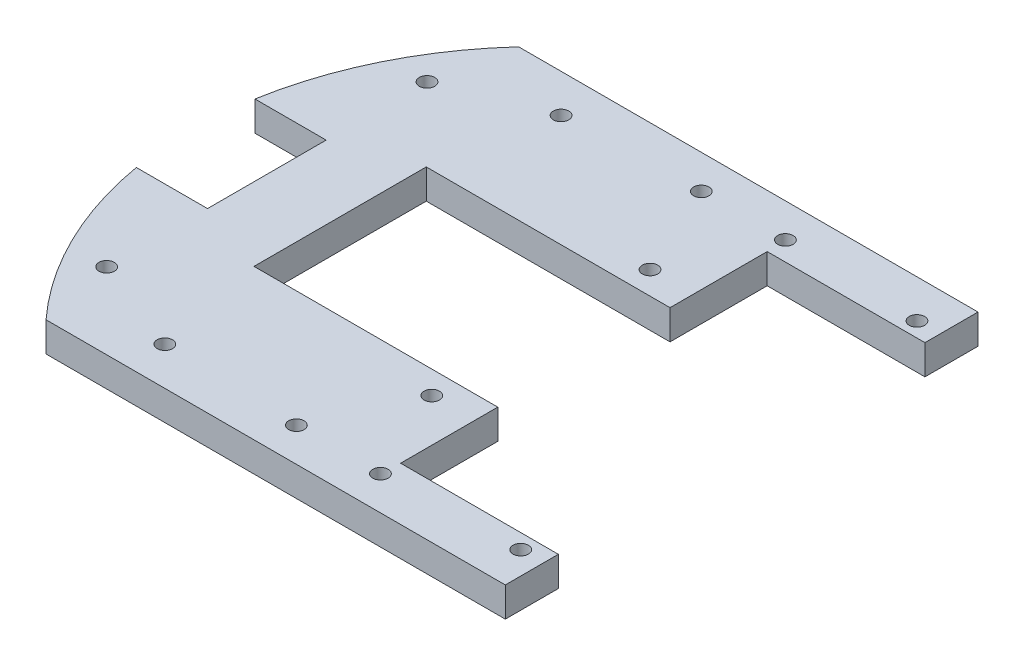
SolidWorks part; units mm, degrees
material "Acrylic (Medium-high impact)"
ref_plane "Front Plane" through (0, 0, 0) normal (0, 0, 1) x (1, 0, 0)
ref_plane "Top Plane" through (0, 0, 0) normal (0, 1, 0) x (1, 0, 0)
ref_plane "Right Plane" through (0, 0, 0) normal (1, 0, 0) x (0, 0, -1)
sketch "Sketch1" plane through (0, 0, 0) normal (0, 1, 0) x (1, 0, 0)
  line L0 (33.7767, 7.1689) -> (0, 7.1689)
  line L1 (-30.9328, 38.3108) -> (-15.6928, 38.3108)
  line L2 (-15.6928, 38.3108) -> (-15.6928, 12.9108)
  line L3 (0, -24.9927) -> (85.9683, -24.9927)
  line L4 (33.7767, 7.1689) -> (52.1917, 7.1689)
  line L5 (52.1917, 7.1689) -> (52.1917, -13.6322)
  line L6 (52.1917, -13.6322) -> (85.9683, -13.6322)
  line L7 (85.9683, -13.6322) -> (85.9683, -24.9927)
  line L8 (42.9842, 2.2428) -> (42.9842, 7.1689) construction
  line L9 (81.0842, -16.8072) -> (81.0842, -13.6322) construction
  line L10 (81.0842, -16.8072) -> (85.9683, -16.8072) construction
  line L11 (4.8842, -16.8072) -> (4.8842, -13.6322) construction
  line L12 (4.8842, -16.8072) -> (0, -16.8072) construction
  line L14 (36.4834, -24.9927) -> (49.4834, -24.9927) construction
  line L15 (-30.9328, 25.6108) -> (90.9164, 25.6108) construction
  line L16 (-30.9328, 38.3108) -> (-30.9328, 12.9108) construction
  line L17 (90.9164, 24.0233) -> (90.9164, 27.1983) construction
  line L18 (4.8842, 68.0288) -> (0, 68.0288) construction
  line L19 (4.8842, 68.0288) -> (4.8842, 64.8538) construction
  line L20 (81.0842, 68.0288) -> (85.9683, 68.0288) construction
  line L21 (81.0842, 68.0288) -> (81.0842, 64.8538) construction
  line L22 (42.9842, 48.9788) -> (42.9842, 44.0527) construction
  line L23 (85.9683, 64.8538) -> (85.9683, 76.2143)
  line L24 (52.1917, 64.8538) -> (85.9683, 64.8538)
  line L25 (52.1917, 44.0527) -> (52.1917, 64.8538)
  line L26 (33.7767, 44.0527) -> (52.1917, 44.0527)
  line L27 (0, 76.2143) -> (85.9683, 76.2143)
  line L28 (-15.6928, 12.9108) -> (-30.9328, 12.9108)
  line L30 (33.7767, 44.0527) -> (0, 44.0527)
  line L32 (0, 76.2143) -> (-12.3719, 76.2143)
  line L33 (0, 44.0527) -> (0, 7.1689)
  line L34 (0, -24.9927) -> (-12.3719, -24.9927)
  circle A0 centre (4.8842, -16.8072) radius 1.651
  circle A1 centre (81.0842, -16.8072) radius 1.651
  circle A2 centre (42.9842, 2.2428) radius 1.651
  circle A3 centre (33.9834, -17.7427) radius 1.651
  circle A4 centre (51.9834, -17.7427) radius 1.651
  circle A5 centre (42.9842, 2.2428) radius 1.651 construction
  circle A6 centre (51.9834, 68.9643) radius 1.651
  circle A7 centre (33.9834, 68.9643) radius 1.651
  circle A8 centre (42.9842, 48.9788) radius 1.651
  circle A9 centre (81.0842, 68.0288) radius 1.651
  circle A10 centre (4.8842, 68.0288) radius 1.651
  arc A11 (-30.9328, 12.9108) -> (110.2551, -7.5497) centre (42.9842, 25.6108) ccw construction
  arc A12 (-12.3719, 76.2143) -> (-30.9328, 38.3108) centre (42.9842, 25.6108) ccw
  arc A13 (110.2551, 58.7714) -> (-30.9328, 38.3108) centre (42.9842, 25.6108) ccw construction
  arc A14 (-12.3719, -24.9927) -> (-30.9328, 12.9108) centre (42.9842, 25.6108) cw
  circle A15 centre (-15.6928, 59.9008) radius 1.651
  circle A16 centre (-15.6928, -8.6792) radius 1.651
  circle A17 centre (-15.6928, 59.9008) radius 1.651 construction
  dimension "D1" = 33.7767
  dimension "D2" = 3.175
  dimension "D3" = 4.9261
  dimension "D4" = 15.6928
  dimension "D5" = 85.9683
extrude "Boss-Extrude1" add sketch "Sketch1" along normal blind 6.35
